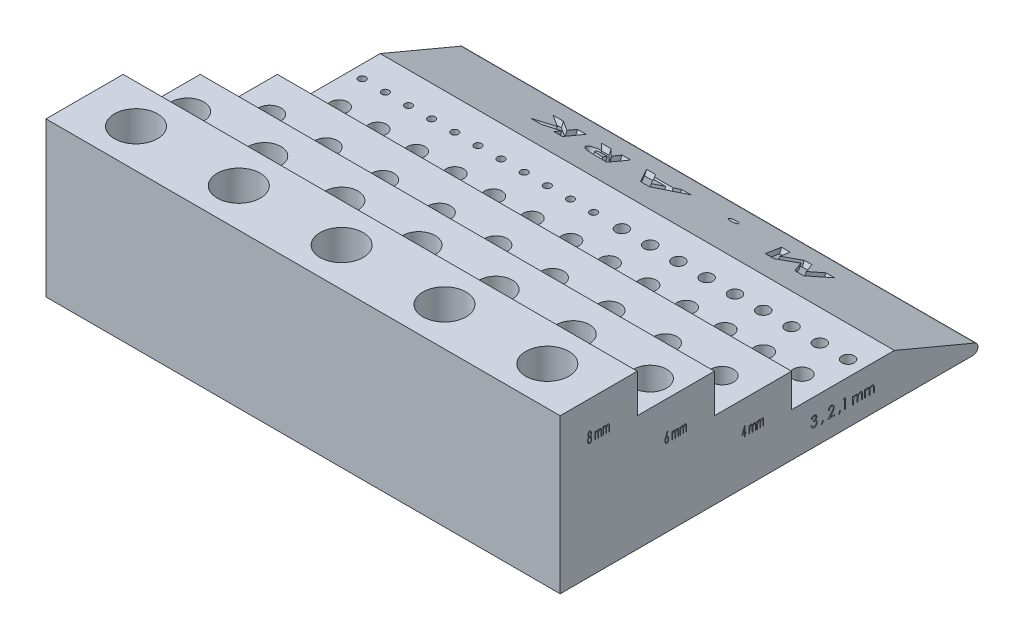
SolidWorks part; units mm, degrees
ref_plane "Front Plane" through (0, 0, 0) normal (0, 0, 1) x (1, 0, 0)
ref_plane "Top Plane" through (0, 0, 0) normal (0, 1, 0) x (1, 0, 0)
ref_plane "Right Plane" through (0, 0, 0) normal (1, 0, 0) x (0, 0, -1)
sketch "Sketch1" plane through (0, 0, 0) normal (1, 0, 0) x (0, 0, -1)
  line L0 (0, -1000) -> (0, 49000) construction
  line L1 (-1000, 0) -> (49000, 0) construction
  line L2 (-26.5708, 30) -> (-41.5708, 30)
  line L3 (-41.5708, 30) -> (-41.5708, 0)
  line L4 (-41.5708, 0) -> (38.6966, 0)
  line L5 (39.084, 1.9219) -> (23.4292, 8.5)
  line L6 (23.4292, 8.5) -> (3.4292, 8.5)
  line L7 (3.4292, 8.5) -> (3.4292, 15)
  line L8 (3.4292, 15) -> (-11.5708, 15)
  line L9 (-11.5708, 15) -> (-11.5708, 22.5)
  line L10 (-11.5708, 22.5) -> (-26.5708, 22.5)
  line L11 (-26.5708, 22.5) -> (-26.5708, 30)
  arc A1 (38.6966, 0) -> (39.084, 1.9219) centre (38.6966, 1) ccw
  dimension "D3" = 1
  dimension "D1" = 30
  dimension "D2" = 15
  dimension "D4" = 41.5708
  dimension "D5" = 7.5
  dimension "D6" = 6.5
  dimension "D7" = 80.2675
  dimension "D8" = 20
extrude "Boss-Extrude1" add sketch "Sketch1" along normal blind 100
sketch "Sketch2" plane through (0, 15.5919, -6.5516) normal (0, 0.9219, -0.3874) x (1, 0, 0)
  line L0 (50, -969.7802) -> (50, 49030.2198) construction
  line L1 (100, 18.307) -> (0, 18.307) construction
  line L2 (90, 30.3194) -> (10, 30.3194) construction
  text T0 "<b>M . ARK</b>" font "Century Gothic" height 5
  point P5 (50, 18.307)
  point P11 (50, 30.3194)
  dimension "D1" = 80
extrude "Cut-Extrude1" cut sketch "Sketch2" against normal blind 1
sketch "Sketch3" plane through (0, 30, 0) normal (0, 1, 0) x (1, 0, 0)
  line L0 (50, -1041.5708) -> (50, 48958.4292) construction
  line L1 (100, -41.5708) -> (0, -41.5708) construction
  line L2 (-900, -34.0708) -> (49100, -34.0708) construction
  line L3 (100, -26.5708) -> (100, -41.5708) construction
  line L4 (50, -34.0708) -> (70, -34.0708) construction
  line L5 (50, -34.0708) -> (30, -34.0708) construction
  circle A0 centre (50, -34.0708) radius 4.2
  circle A1 centre (70, -34.0708) radius 4.2
  circle A2 centre (90, -34.0708) radius 4.2
  circle A3 centre (30, -34.0708) radius 4.2
  circle A4 centre (10, -34.0708) radius 4.2
  point P5 (50, -41.5708)
  point P10 (100, -34.0708)
  dimension "D1" = 8.4
  dimension "D3" = 20
  dimension "D5" = 20
  dimension "D2" = 3
  dimension "D4" = 3
extrude "Cut-Extrude2" cut sketch "Sketch3" against normal blind 20
sketch "Sketch4" plane through (0, 22.5, 0) normal (0, 1, 0) x (1, 0, 0)
  line L0 (50, -1041.5708) -> (50, 48958.4292) construction
  line L1 (100, -41.5708) -> (0, -41.5708) construction
  line L2 (100, -11.5708) -> (100, -26.5708) construction
  line L3 (50, -19.0708) -> (65, -19.0708) construction
  circle A0 centre (50, -19.0708) radius 3.2
  circle A1 centre (65, -19.0708) radius 3.2
  circle A2 centre (80, -19.0708) radius 3.2
  circle A3 centre (95, -19.0708) radius 3.2
  circle A4 centre (5, -19.0708) radius 3.2
  circle A5 centre (20, -19.0708) radius 3.2
  circle A6 centre (35, -19.0708) radius 3.2
  point P5 (50, -41.5708)
  point P9 (100, -19.0708)
  dimension "D1" = 6.4
  dimension "D3" = 15
  dimension "D2" = 4
extrude "Cut-Extrude3" cut sketch "Sketch4" against normal blind 17
sketch "Sketch5" plane through (0, 15, 0) normal (0, 1, 0) x (1, 0, 0)
  line L0 (50, -1026.5708) -> (50, 48973.4292) construction
  line L1 (100, -26.5708) -> (0, -26.5708) construction
  line L2 (100, 3.4292) -> (100, -11.5708) construction
  line L3 (50, -4.0708) -> (61, -4.0708) construction
  circle A0 centre (50, -4.0708) radius 2.2
  circle A1 centre (61, -4.0708) radius 2.2
  circle A2 centre (72, -4.0708) radius 2.2
  circle A3 centre (83, -4.0708) radius 2.2
  circle A4 centre (94, -4.0708) radius 2.2
  circle A5 centre (6, -4.0708) radius 2.2
  circle A6 centre (17, -4.0708) radius 2.2
  circle A7 centre (28, -4.0708) radius 2.2
  circle A8 centre (39, -4.0708) radius 2.2
  point P5 (50, -26.5708)
  point P10 (100, -4.0708)
  dimension "D1" = 4.4
  dimension "D3" = 11
  dimension "D2" = 5
extrude "Cut-Extrude4" cut sketch "Sketch5" against normal blind 10
sketch "Sketch6" plane through (0, 8.5, 0) normal (0, 1, 0) x (1, 0, 0)
  line L0 (50, 10.4292) -> (57.5, 10.4292) construction
  line L1 (-900, 17.4292) -> (49100, 17.4292) construction
  line L2 (-900.941, 10.4292) -> (49099.059, 10.4292) construction
  line L3 (50, -1041.5708) -> (50, 48958.4292) construction
  line L4 (100, -41.5708) -> (0, -41.5708) construction
  line L5 (100, 3.4292) -> (0, 3.4292) construction
  line L6 (75, 17.4292) -> (80.5, 17.4292) construction
  line L7 (75, 3.4292) -> (75, 23.4292) construction
  line L8 (100, 3.4292) -> (0, 3.4292) construction
  line L9 (100, 23.4292) -> (0, 23.4292) construction
  line L10 (25, 17.4292) -> (29.5, 17.4292) construction
  line L11 (25, 3.4292) -> (25, 23.4292) construction
  circle A14 centre (75, 17.4292) radius 1.2
  circle A16 centre (50, 10.4292) radius 1.7
  circle A17 centre (57.5, 10.4292) radius 1.7
  circle A18 centre (65, 10.4292) radius 1.7
  circle A19 centre (72.5, 10.4292) radius 1.7
  circle A20 centre (80, 10.4292) radius 1.7
  circle A21 centre (87.5, 10.4292) radius 1.7
  circle A22 centre (95, 10.4292) radius 1.7
  circle A23 centre (5, 10.4292) radius 1.7
  circle A24 centre (12.5, 10.4292) radius 1.7
  circle A25 centre (20, 10.4292) radius 1.7
  circle A26 centre (27.5, 10.4292) radius 1.7
  circle A27 centre (35, 10.4292) radius 1.7
  circle A28 centre (42.5, 10.4292) radius 1.7
  circle A29 centre (80.5, 17.4292) radius 1.2
  circle A30 centre (86, 17.4292) radius 1.2
  circle A31 centre (91.5, 17.4292) radius 1.2
  circle A32 centre (58.5, 17.4292) radius 1.2
  circle A33 centre (64, 17.4292) radius 1.2
  circle A34 centre (69.5, 17.4292) radius 1.2
  circle A35 centre (97, 17.4292) radius 1.2
  circle A36 centre (53, 17.4292) radius 1.2
  circle A37 centre (25, 17.4292) radius 0.7
  circle A38 centre (29.5, 17.4292) radius 0.7
  circle A39 centre (34, 17.4292) radius 0.7
  circle A40 centre (38.5, 17.4292) radius 0.7
  circle A41 centre (43, 17.4292) radius 0.7
  circle A42 centre (47.5, 17.4292) radius 0.7
  circle A43 centre (2.5, 17.4292) radius 0.7
  circle A44 centre (7, 17.4292) radius 0.7
  circle A45 centre (11.5, 17.4292) radius 0.7
  circle A46 centre (16, 17.4292) radius 0.7
  circle A47 centre (20.5, 17.4292) radius 0.7
  point P9 (50, -41.5708)
  dimension "D4" = 3.4
  dimension "D7" = 5.5
  dimension "D6" = 2.4
  dimension "D9" = 1.4
  dimension "D1" = 7
  dimension "D2" = 7
  dimension "D3" = 25
  dimension "D5" = 7.5
  dimension "D8" = 5.5
  dimension "D10" = 4.5
extrude "Cut-Extrude5" cut sketch "Sketch6" against normal blind 5
sketch "Sketch7" plane through (100, 0, 0) normal (1, 0, 0) x (0, 0, -1)
  line L0 (-34.0708, -970) -> (-34.0708, 49030) construction
  line L1 (-26.5708, 30) -> (-41.5708, 30) construction
  line L2 (-19.0708, -977.5) -> (-19.0708, 49022.5) construction
  line L3 (-11.5708, 22.5) -> (-26.5708, 22.5) construction
  line L4 (-4.0708, -985) -> (-4.0708, 49015) construction
  line L5 (3.4292, 15) -> (-11.5708, 15) construction
  line L6 (13.4292, -991.5) -> (13.4292, 49008.5) construction
  line L7 (23.4292, 8.5) -> (3.4292, 8.5) construction
  line L8 (-38.0708, 22.5) -> (-30.0708, 22.5) construction
  line L9 (-23.0708, 15) -> (-15.0708, 15) construction
  line L10 (-8.0708, 8.5) -> (-0.0708, 8.5) construction
  line L11 (4.4292, 3.3368) -> (22.4292, 3.3368) construction
  text T0 "8 mm" font "Century Gothic" height 2
  text T1 "6 mm" font "Century Gothic" height 2
  text T2 "4 mm" font "Century Gothic" height 2
  text T3 "3 , 2 ,1 mm" font "Century Gothic" height 2
  point P5 (-34.0708, 30)
  point P10 (-19.0708, 22.5)
  point P15 (-4.0708, 15)
  point P20 (13.4292, 8.5)
  point P23 (-34.0708, 22.5)
  point P26 (-19.0708, 15)
  point P29 (-4.0708, 8.5)
  point P32 (13.4292, 3.3368)
  dimension "D1" = 8
  dimension "D2" = 18
extrude "Cut-Extrude6" cut sketch "Sketch7" against normal blind 1
